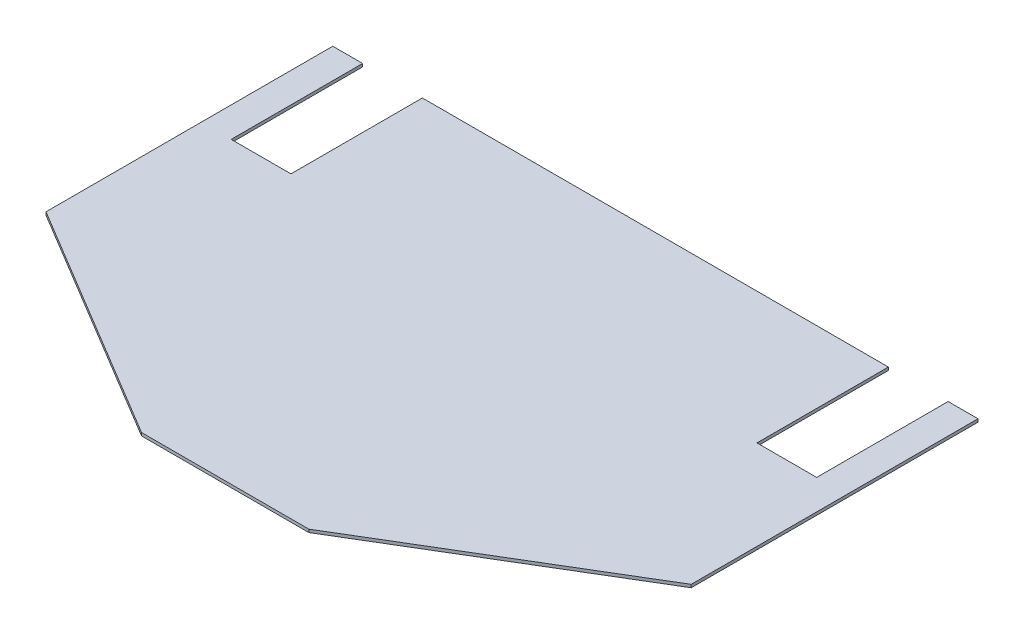
SolidWorks part; units mm, degrees
material "6061 Alloy"
ref_plane "Front Plane" through (0, 0, 0) normal (0, 0, 1) x (1, 0, 0)
ref_plane "Top Plane" through (0, 0, 0) normal (0, 1, 0) x (1, 0, 0)
ref_plane "Right Plane" through (0, 0, 0) normal (1, 0, 0) x (0, 0, -1)
sketch "Sketch1" plane through (0, 0, 0) normal (0, 1, 0) x (1, 0, 0)
  line L0 (-44.45, 0) -> (44.45, 0)
  line L1 (44.45, 0) -> (171.45, 76.2)
  line L2 (171.45, 76.2) -> (171.45, 228.6)
  line L3 (171.45, 228.6) -> (-171.45, 228.6)
  line L4 (0, 228.6) -> (0, 0) construction
  line L5 (-44.45, 0) -> (-171.45, 76.2)
  line L6 (-171.45, 76.2) -> (-171.45, 228.6)
  line L7 (-155.575, 228.6) -> (-155.575, 158.75)
  line L8 (155.575, 228.6) -> (123.825, 228.6)
  line L9 (155.575, 228.6) -> (155.575, 158.75)
  line L10 (155.575, 158.75) -> (123.825, 158.75)
  line L11 (123.825, 228.6) -> (123.825, 158.75)
  line L12 (-123.825, 228.6) -> (-123.825, 158.75)
  line L13 (-155.575, 158.75) -> (-123.825, 158.75)
  dimension "D1" = 228.6
  dimension "D2" = 44.45
  dimension "D3" = 152.4
  dimension "D4" = 171.45
  dimension "D5" = 31.75
  dimension "D6" = 69.85
  dimension "D7" = 15.875
extrude "Boss-Extrude2" add sketch "Sketch1" along normal blind 1.5875 contours L4 L3 L12 L13 L7 L6 L5 L0 | L3 L4 L0 L1 L2 L9 L10 L11
